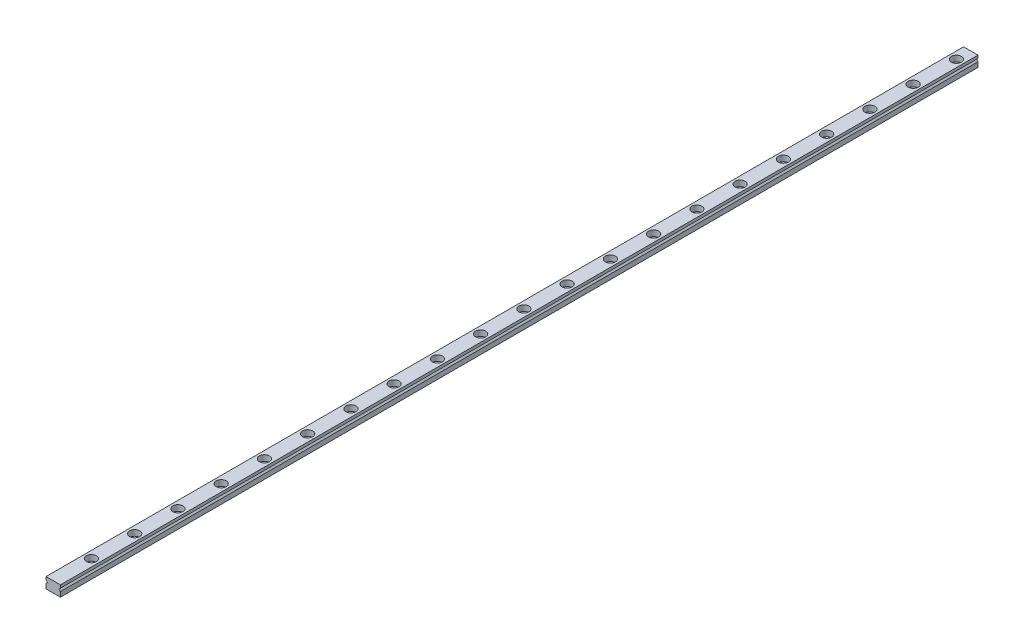
SolidWorks part; units mm, degrees
material "AISI 304"
ref_plane "前视基准面" through (0, 0, 0) normal (0, 0, 1) x (1, 0, 0)
ref_plane "上视基准面" through (0, 0, 0) normal (0, 1, 0) x (1, 0, 0)
ref_plane "右视基准面" through (0, 0, 0) normal (1, 0, 0) x (0, 0, -1)
sketch "Sketch1" plane through (0, 0, 0) normal (0, 0, 1) x (1, 0, 0)
  line L0 (0, 0) -> (0, 3.7)
  line L1 (0, 3.7) -> (5, 3.7)
  line L2 (5, 3.7) -> (5, 0)
  line L3 (5, 0) -> (0, 0)
  dimension "D1" = 3.7
  dimension "D2" = 5
extrude "Boss-Extrude1" add sketch "Sketch1" against normal blind 400
sketch "Sketch2" plane through (0, 3.7, 0) normal (0, 1, 0) x (1, 0, 0)
  line L0 (2.5, -0.9977) -> (2.5, 11.7262) construction
  line L1 (-6.0403, 5) -> (12.1202, 5) construction
  line L2 (5, 0) -> (0, 0) construction
  line L3 (5, 400) -> (5, 0) construction
  circle A0 centre (2.5, 5) radius 1.75
  circle A1 centre (2.5, 20) radius 1.75
  circle A2 centre (2.5, 35) radius 1.75
  circle A3 centre (2.5, 50) radius 1.75
  circle A4 centre (2.5, 65) radius 1.75
  circle A5 centre (2.5, 80) radius 1.75
  circle A6 centre (2.5, 95) radius 1.75
  circle A7 centre (2.5, 110) radius 1.75
  circle A8 centre (2.5, 125) radius 1.75
  circle A9 centre (2.5, 140) radius 1.75
  circle A10 centre (2.5, 155) radius 1.75
  circle A11 centre (2.5, 170) radius 1.75
  circle A12 centre (2.5, 185) radius 1.75
  circle A13 centre (2.5, 200) radius 1.75
  circle A14 centre (2.5, 215) radius 1.75
  circle A15 centre (2.5, 230) radius 1.75
  circle A16 centre (2.5, 245) radius 1.75
  circle A17 centre (2.5, 260) radius 1.75
  circle A18 centre (2.5, 275) radius 1.75
  circle A19 centre (2.5, 290) radius 1.75
  circle A20 centre (2.5, 305) radius 1.75
  circle A21 centre (2.5, 320) radius 1.75
  circle A22 centre (2.5, 335) radius 1.75
  circle A23 centre (2.5, 350) radius 1.75
  circle A24 centre (2.5, 365) radius 1.75
  circle A25 centre (2.5, 380) radius 1.75
  circle A26 centre (2.5, 395) radius 1.75
  dimension "D3" = 3.5
  dimension "D1" = 5
  dimension "D2" = 2.5
  dimension "D5" = 390
  dimension "D4" = 27
extrude "Cut-Extrude1" cut sketch "Sketch2" against normal blind 2
sketch "Sketch3" plane through (0, 1.7, 0) normal (0, 1, 0) x (1, 0, 0)
  circle A0 centre (2.5, 5) radius 1
  circle A1 centre (2.5, 20) radius 1
  circle A2 centre (2.5, 35) radius 1
  circle A3 centre (2.5, 50) radius 1
  circle A4 centre (2.5, 65) radius 1
  circle A5 centre (2.5, 80) radius 1
  circle A6 centre (2.5, 95) radius 1
  circle A7 centre (2.5, 110) radius 1
  circle A8 centre (2.5, 125) radius 1
  circle A9 centre (2.5, 140) radius 1
  circle A10 centre (2.5, 155) radius 1
  circle A11 centre (2.5, 170) radius 1
  circle A12 centre (2.5, 185) radius 1
  circle A13 centre (2.5, 200) radius 1
  circle A14 centre (2.5, 215) radius 1
  circle A15 centre (2.5, 230) radius 1
  circle A16 centre (2.5, 245) radius 1
  circle A17 centre (2.5, 260) radius 1
  circle A18 centre (2.5, 275) radius 1
  circle A19 centre (2.5, 290) radius 1
  circle A20 centre (2.5, 305) radius 1
  circle A21 centre (2.5, 320) radius 1
  circle A22 centre (2.5, 335) radius 1
  circle A23 centre (2.5, 350) radius 1
  circle A24 centre (2.5, 365) radius 1
  circle A25 centre (2.5, 380) radius 1
  circle A26 centre (2.5, 395) radius 1
  dimension "D1" = 2
  dimension "D3" = 390
  dimension "D2" = 27
extrude "Cut-Extrude2" cut sketch "Sketch3" against normal through all
sketch "Sketch4" plane through (0, 0, 0) normal (0, 0, 1) x (1, 0, 0)
  line L0 (2.5, 3.8064) -> (2.5, -0.1865) construction
  line L1 (5, 0) -> (5, 3.7) construction
  line L2 (0, 2.7) -> (0.5, 2.2)
  line L3 (0, 3.7) -> (0, 0) construction
  line L4 (0.5, 2.2) -> (0, 1.7)
  line L5 (0, 2.7) -> (0, 1.7)
  line L6 (5, 2.7) -> (4.5, 2.2)
  line L7 (4.5, 2.2) -> (5, 1.7)
  line L8 (5, 2.7) -> (5, 1.7)
  dimension "D1" = 2.5
  dimension "D2" = 45
  dimension "D3" = 45
  dimension "D4" = 1
  dimension "D5" = 0.5
extrude "Cut-Extrude3" cut sketch "Sketch4" against normal through all
sketch "草图1" plane through (0, 3.7, 0) normal (0, 1, 0) x (1, 0, 0)
  line L0 (2.5, 81.75) -> (15.1136, 81.75)
  line L1 (15.1136, 81.75) -> (15.1136, -29.6948)
  line L2 (15.1136, -29.6948) -> (-58.541, -29.6948)
  line L3 (-58.541, -29.6948) -> (-58.541, 81.75)
  line L4 (-58.541, 81.75) -> (2.5, 81.75)
  circle A0 centre (2.5, 80) radius 1.75 construction
  circle A1 centre (2.5, 80) radius 1.75 construction
extrude "切除-拉伸1" cut sketch "草图1" against normal blind 10
